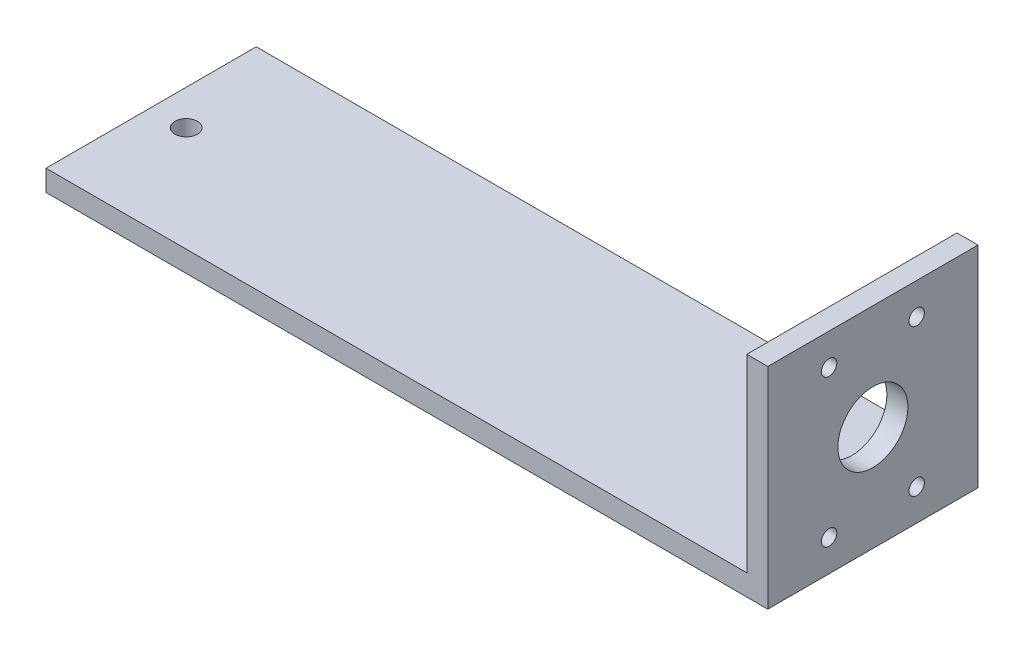
SolidWorks part; units mm, degrees
ref_plane "Front Plane" through (0, 0, 0) normal (0, 0, 1) x (1, 0, 0)
ref_plane "Top Plane" through (0, 0, 0) normal (0, 1, 0) x (1, 0, 0)
ref_plane "Right Plane" through (0, 0, 0) normal (1, 0, 0) x (0, 0, -1)
sketch "Sketch1" plane through (0, 0, 0) normal (0, 1, 0) x (1, 0, 0)
  line L1 (-50, 15) -> (50, 15)
  line L2 (-50, 15) -> (-50, -15)
  line L3 (-50, -15) -> (50, -15)
  line L4 (50, 15) -> (50, -15)
  line L5 (-50, 15) -> (50, -15) construction
  line L6 (-50, -15) -> (50, 15) construction
  point P0 (0, 0)
  dimension "D1" = 100
  dimension "D2" = 30
extrude "Boss-Extrude1" add sketch "Sketch1" along normal blind 3
sketch "Sketch2" plane through (0, 3, 0) normal (0, 1, 0) x (1, 0, 0)
  line L0 (0, -1.65) -> (0, 1.65) construction
  circle A0 centre (45, 0) radius 1.6
  circle A1 centre (-45, 0) radius 1.6
  dimension "D1" = 45
  dimension "D2" = 3.2
extrude "Cut-Extrude1" cut sketch "Sketch2" against normal through all
sketch "Sketch5" plane through (50, 0, 0) normal (1, 0, 0) x (0, 0, -1)
  line L1 (-15, 0) -> (15, 0)
  line L2 (-15, 0) -> (-15, 30)
  line L3 (-15, 30) -> (15, 30)
  line L4 (15, 0) -> (15, 30)
  dimension "D1" = 30
  dimension "D2" = 30
extrude "Boss-Extrude2" add sketch "Sketch5" along normal blind 3
sketch "Sketch6" plane through (53, 0, 0) normal (1, 0, 0) x (0, 0, -1)
  line L0 (-15, 30) -> (-6.25, 21.25) construction
  line L1 (0, 16.5) -> (0, -16.5) construction
  line L2 (-6.25, 25.5) -> (-5.15, 25.5)
  line L3 (-6.25, 25.5) -> (-6.25, 21.25)
  line L4 (-6.25, 4.5) -> (-5.15, 4.5)
  line L5 (6.25, 25.5) -> (6.25, 24.4)
  line L6 (-6.25, 25.5) -> (-5.6874, 24.5548) construction
  line L7 (-6.25, 4.5) -> (-5.6874, 5.4452) construction
  line L8 (-15, 15) -> (6.25, 15) construction
  line L9 (-15, 30) -> (-15, 0) construction
  line L11 (-6.25, 5.6) -> (-6.25, 4.5)
  line L13 (5.6874, 5.4452) -> (6.25, 4.5) construction
  line L14 (5.15, 25.5) -> (6.25, 25.5)
  line L15 (5.6874, 24.5548) -> (6.25, 25.5) construction
  line L16 (6.25, 5.6) -> (6.25, 4.5)
  line L17 (5.15, 4.5) -> (6.25, 4.5)
  circle A0 centre (-6.25, 25.5) radius 1.1
  circle A1 centre (6.25, 25.5) radius 1.1
  circle A2 centre (6.25, 4.5) radius 1.1
  circle A3 centre (-6.25, 4.5) radius 1.1
  point P6 (0, 15)
  dimension "D1" = 21
  dimension "D3" = 2.2
  dimension "D2" = 12.5
extrude "Cut-Extrude2" cut sketch "Sketch6" against normal through all contours A0 | A1 | A3 | A2
sketch "Sketch7" plane through (53, 0, 0) normal (1, 0, 0) x (0, 0, -1)
  circle A0 centre (0, 15) radius 5
  dimension "D1" = 10
extrude "Cut-Extrude3" cut sketch "Sketch7" against normal through all
